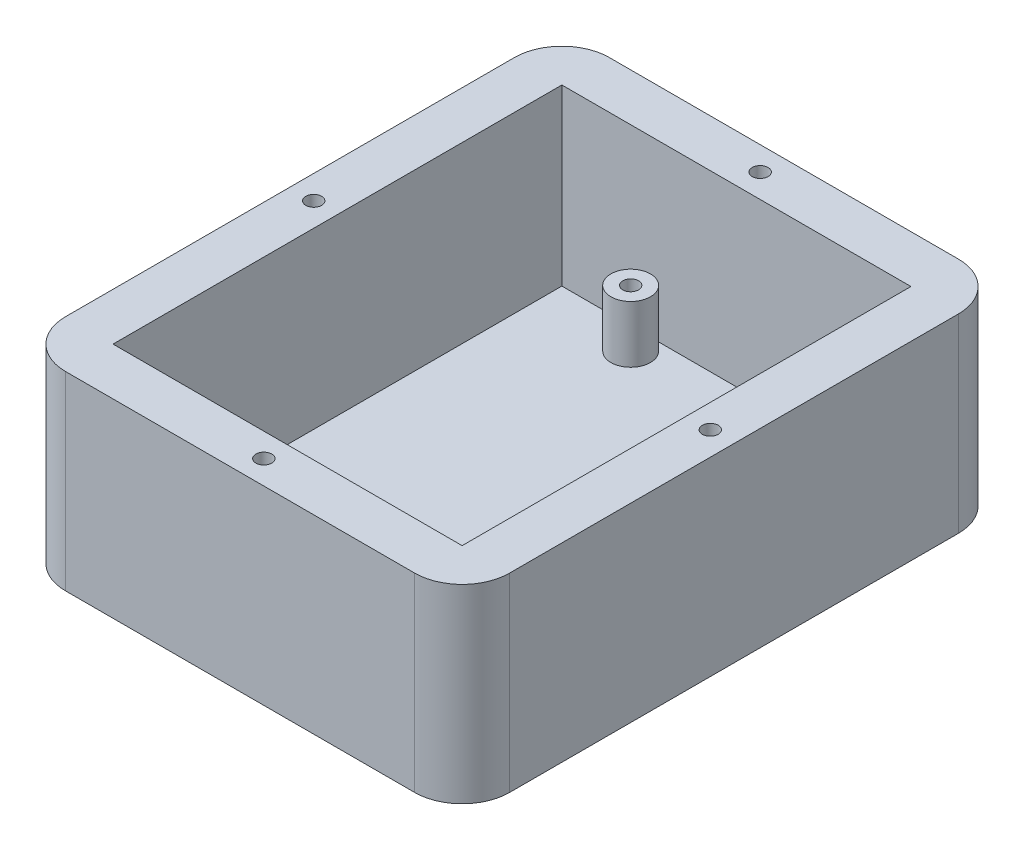
SolidWorks part; units mm, degrees
ref_plane "Front Plane" through (0, 0, 0) normal (0, 0, 1) x (1, 0, 0)
ref_plane "Top Plane" through (0, 0, 0) normal (0, 1, 0) x (1, 0, 0)
ref_plane "Right Plane" through (0, 0, 0) normal (1, 0, 0) x (0, 0, -1)
sketch "Sketch1" plane through (0, 0, 0) normal (0, 1, 0) x (1, 0, 0)
  line L1 (3.175, 0) -> (73.175, 0)
  line L2 (0, 3.175) -> (0, 93.175)
  line L3 (3.175, 96.35) -> (73.175, 96.35)
  line L4 (76.35, 3.175) -> (76.35, 93.175)
  arc A0 (3.175, 0) -> (0, 3.175) centre (3.175, 3.175) cw
  arc A1 (73.175, 0) -> (76.35, 3.175) centre (73.175, 3.175) ccw
  arc A2 (73.175, 96.35) -> (76.35, 93.175) centre (73.175, 93.175) cw
  arc A3 (0, 93.175) -> (3.175, 96.35) centre (3.175, 93.175) cw
  point P7 (0, 0)
  point P10 (76.35, 0)
  point P13 (76.35, 96.35)
  dimension "D3" = 3.175
  dimension "D1" = 76.35
  dimension "D2" = 96.35
extrude "Boss-Extrude1" add sketch "Sketch1" along normal blind 38.1
sketch "Sketch2" plane through (0, 38.1, 0) normal (0, 1, 0) x (1, 0, 0)
  line L8 (3.175, 3.175) -> (73.175, 3.175)
  line L9 (73.175, 3.175) -> (73.175, 93.175)
  line L10 (73.175, 93.175) -> (3.175, 93.175)
  line L11 (3.175, 93.175) -> (3.175, 3.175)
  line L12 (3.175, 3.175) -> (73.175, 3.175)
  line L13 (73.175, 3.175) -> (73.175, 93.175)
  line L14 (73.175, 93.175) -> (3.175, 93.175)
  line L15 (3.175, 93.175) -> (3.175, 3.175)
  dimension "D1" = 3.175
extrude "Cut-Extrude1" cut sketch "Sketch2" against normal offset from surface (34.925 mm away) 3.175 up to face at (38.175, 0, -48.175)
sketch "Sketch3" plane through (0, 3.175, 0) normal (0, 1, 0) x (1, 0, 0)
  line L0 (3.175, 93.175) -> (3.175, 3.175) construction
  line L1 (6.005, 92.175) -> (70.345, 92.175) construction
  line L2 (6.005, 92.175) -> (6.005, 4.175) construction
  line L3 (6.005, 4.175) -> (70.345, 4.175) construction
  line L4 (70.345, 92.175) -> (70.345, 4.175) construction
  line L5 (73.175, 93.175) -> (3.175, 93.175) construction
  circle A0 centre (39.705, 8.975) radius 1.5875
  circle A1 centre (21.372, 88.775) radius 1.5875
  circle A2 centre (21.372, 88.775) radius 3.9688
  circle A3 centre (39.705, 8.975) radius 3.9687
  point P6 (3.175, 48.175)
  point P7 (6.005, 48.175)
  point P10 (38.175, 93.175)
  point P11 (38.175, 92.175)
  dimension "D3" = 3.175
  dimension "D8" = 7.9375
  dimension "D9" = 7.9375
  dimension "D1" = 64.34
  dimension "D2" = 88
  dimension "D4" = 4.8
  dimension "D5" = 33.7
  dimension "D6" = 84.6
  dimension "D7" = 15.367
extrude "Boss-Extrude2" add sketch "Sketch3" along normal blind 11.43
sketch "Sketch4" plane through (0, 0, 0) normal (0, -1, 0) x (1, 0, 0)
  line L0 (-6.35, -3.175) -> (-6.35, -93.175)
  line L1 (3.175, -102.7) -> (73.175, -102.7)
  line L2 (82.7, -93.175) -> (82.7, -3.175)
  line L3 (73.175, 6.35) -> (3.175, 6.35)
  line L4 (0, -3.175) -> (0, -93.175)
  line L5 (3.175, -96.35) -> (73.175, -96.35)
  line L6 (76.35, -93.175) -> (76.35, -3.175)
  line L7 (73.175, 0) -> (3.175, 0)
  line L8 (0, -3.175) -> (0, -93.175)
  line L9 (3.175, -96.35) -> (73.175, -96.35)
  line L10 (76.35, -93.175) -> (76.35, -3.175)
  line L11 (73.175, 0) -> (3.175, 0)
  arc A0 (3.175, 6.35) -> (-6.35, -3.175) centre (3.175, -3.175) ccw
  arc A1 (-6.35, -93.175) -> (3.175, -102.7) centre (3.175, -93.175) ccw
  arc A2 (73.175, -102.7) -> (82.7, -93.175) centre (73.175, -93.175) ccw
  arc A3 (82.7, -3.175) -> (73.175, 6.35) centre (73.175, -3.175) ccw
  arc A4 (3.175, 0) -> (0, -3.175) centre (3.175, -3.175) ccw
  arc A5 (0, -93.175) -> (3.175, -96.35) centre (3.175, -93.175) ccw
  arc A6 (73.175, -96.35) -> (76.35, -93.175) centre (73.175, -93.175) ccw
  arc A7 (76.35, -3.175) -> (73.175, 0) centre (73.175, -3.175) ccw
  arc A8 (3.175, 0) -> (0, -3.175) centre (3.175, -3.175) ccw
  arc A9 (0, -93.175) -> (3.175, -96.35) centre (3.175, -93.175) ccw
  arc A10 (73.175, -96.35) -> (76.35, -93.175) centre (73.175, -93.175) ccw
  arc A11 (76.35, -3.175) -> (73.175, 0) centre (73.175, -3.175) ccw
  dimension "D1" = 0
  dimension "D2" = 6.35
extrude "Boss-Extrude3" add sketch "Sketch4" against normal up to surface (38.1 mm away) up to face at (38.175, 38.1, -48.175)
sketch "Sketch5" plane through (0, 38.1, 0) normal (0, 1, 0) x (1, 0, 0)
  line L0 (-6.35, 48.175) -> (3.175, 48.175) construction
  line L1 (-6.35, 93.175) -> (-6.35, 3.175) construction
  line L2 (3.175, 93.175) -> (3.175, 3.175) construction
  line L3 (38.175, 102.7) -> (38.175, 93.175) construction
  line L4 (73.175, 102.7) -> (3.175, 102.7) construction
  line L5 (73.175, 93.175) -> (3.175, 93.175) construction
  line L6 (38.175, 93.175) -> (38.175, -1.5718) construction
  line L7 (38.175, -1.5718) -> (3.175, 48.175) construction
  line L8 (3.175, 48.175) -> (73.175, 48.175) construction
  line L9 (73.175, 3.175) -> (73.175, 93.175) construction
  circle A0 centre (-1.5875, 48.175) radius 1.5875
  circle A1 centre (38.175, 97.9375) radius 1.5875
  circle A2 centre (38.175, -1.5875) radius 1.5875
  circle A3 centre (77.9375, 48.175) radius 1.5875
  point P16 (38.175, 97.9375)
  point P17 (-1.5875, 48.175)
  dimension "D1" = 3.175
  dimension "D2" = 3.175
extrude "Cut-Extrude2" cut sketch "Sketch5" against normal blind 12.7
sketch "Sketch6" plane through (0, 38.1, 0) normal (0, 1, 0) x (1, 0, 0)
  line L4 (3.175, -6.35) -> (73.175, -6.35)
  line L5 (82.7, 3.175) -> (82.7, 93.175)
  line L6 (73.175, 102.7) -> (3.175, 102.7)
  line L7 (-6.35, 93.175) -> (-6.35, 3.175)
  line L8 (3.175, -6.35) -> (73.175, -6.35)
  line L9 (82.7, 3.175) -> (82.7, 93.175)
  line L10 (73.175, 102.7) -> (3.175, 102.7)
  line L11 (-6.35, 93.175) -> (-6.35, 3.175)
  circle A0 centre (38.175, -1.5875) radius 1.5875 construction
  circle A1 centre (77.9375, 48.175) radius 1.5875 construction
  circle A2 centre (38.175, 97.9375) radius 1.5875 construction
  circle A3 centre (-1.5875, 48.175) radius 1.5875 construction
  arc A4 (-6.35, 3.175) -> (3.175, -6.35) centre (3.175, 3.175) ccw
  arc A5 (73.175, -6.35) -> (82.7, 3.175) centre (73.175, 3.175) ccw
  arc A6 (82.7, 93.175) -> (73.175, 102.7) centre (73.175, 93.175) ccw
  arc A7 (3.175, 102.7) -> (-6.35, 93.175) centre (3.175, 93.175) ccw
  arc A8 (-6.35, 3.175) -> (3.175, -6.35) centre (3.175, 3.175) ccw
  arc A9 (73.175, -6.35) -> (82.7, 3.175) centre (73.175, 3.175) ccw
  arc A10 (82.7, 93.175) -> (73.175, 102.7) centre (73.175, 93.175) ccw
  arc A11 (3.175, 102.7) -> (-6.35, 93.175) centre (3.175, 93.175) ccw
  circle A12 centre (38.175, -1.5875) radius 1.5875
  circle A13 centre (77.9375, 48.175) radius 1.5875
  circle A14 centre (38.175, 97.9375) radius 1.5875
  circle A15 centre (-1.5875, 48.175) radius 1.5875
  dimension "D1" = 0
sketch "Sketch7" plane through (0, 3.175, 0) normal (0, 1, 0) x (1, 0, 0)
  line L0 (68.175, 70.175) -> (68.175, 26.175) construction
  line L2 (73.175, 3.175) -> (73.175, 93.175) construction
  circle A0 centre (68.175, 70.175) radius 1.5875
  circle A1 centre (68.175, 26.175) radius 1.5875
  point P8 (73.175, 48.175)
  point P9 (68.175, 48.175)
  dimension "D2" = 3.175
  dimension "D1" = 44
  dimension "D3" = 5
extrude "Cut-Extrude3" cut sketch "Sketch7" against normal up to surface (3.175 mm away) up to face at (38.175, 0, -48.175)
